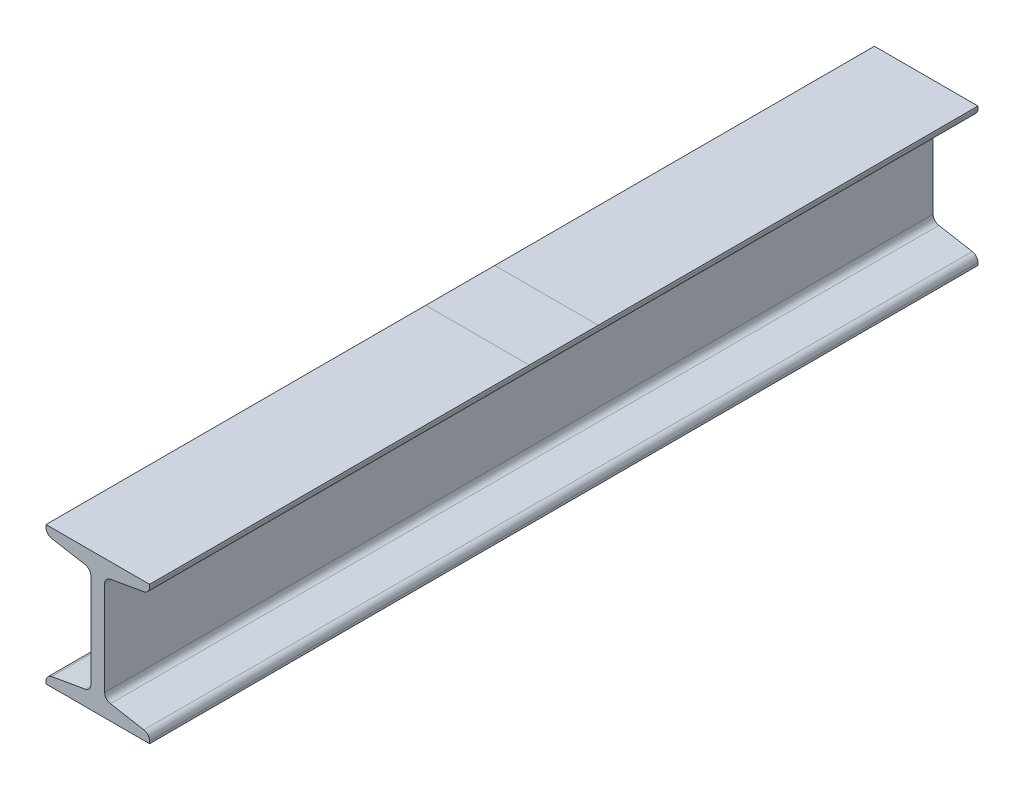
SolidWorks part; units mm, degrees
ref_plane "Front Plane" through (0, 0, 0) normal (0, 0, 1) x (1, 0, 0)
ref_plane "Top Plane" through (0, 0, 0) normal (0, 1, 0) x (1, 0, 0)
ref_plane "Right Plane" through (0, 0, 0) normal (1, 0, 0) x (0, 0, -1)
sketch "Sketch2" plane through (0, 0, 0) normal (0, 0, 1) x (1, 0, 0)
  line L0 (37.5, 50) -> (37.5, 44.0367)
  line L1 (37.5, 44.0367) -> (5, 38.3061)
  line L2 (5, 38.3061) -> (5, -38.3061)
  line L3 (5, -38.3061) -> (37.5, -44.0367)
  line L4 (37.5, -44.0367) -> (37.5, -50)
  line L5 (0, 0) -> (0, 31.6267) construction
  line L6 (0, 0) -> (-7.0282, 0) construction
  line L7 (-37.5, -44.0367) -> (-37.5, -50)
  line L8 (-5, -38.3061) -> (-37.5, -44.0367)
  line L9 (-5, 38.3061) -> (-5, -38.3061)
  line L10 (-37.5, 44.0367) -> (-5, 38.3061)
  line L11 (-37.5, 50) -> (-37.5, 44.0367)
  line L12 (-37.5, 50) -> (37.5, 50)
  line L13 (-37.5, -50) -> (37.5, -50)
  dimension "D1" = 100
  dimension "D2" = 75
  dimension "D3" = 100
  dimension "D4" = 10
extrude "Boss-Extrude1" add sketch "Sketch2" against normal blind 600
sketch "Sketch3" plane through (0, 50, 0) normal (0, 1, 0) x (1, 0, 0)
  line L0 (37.5, 600) -> (37.5, 0) construction
  line L1 (-37.5, 325) -> (37.5, 325)
  line L2 (-37.5, 325) -> (-37.5, 275)
  line L3 (-37.5, 275) -> (37.5, 275)
  line L4 (37.5, 325) -> (37.5, 275)
  line L5 (-37.5, 325) -> (37.5, 275) construction
  line L6 (-37.5, 275) -> (37.5, 325) construction
  point P0 (0, 300)
  dimension "D1" = 50
  dimension "D2" = 300
split line "Split Line1"
sketch "Sketch4" plane through (0, -50, 0) normal (0, -1, 0) x (1, 0, 0)
  line L0 (37.5, -600) -> (37.5, 0) construction
  line L1 (-37.5, 0) -> (37.5, 0)
  line L2 (-37.5, 0) -> (-37.5, -40)
  line L3 (-37.5, -40) -> (37.5, -40)
  line L4 (37.5, 0) -> (37.5, -40)
  line L6 (-37.5, -600) -> (37.5, -600)
  line L7 (-37.5, -600) -> (-37.5, -560)
  line L8 (-37.5, -560) -> (37.5, -560)
  line L9 (37.5, -600) -> (37.5, -560)
  dimension "D1" = 40
  dimension "D2" = 40
split line "Split Line2"
fillet "Fillet1" radius 5 8 edges at (37.5, 44.0367, -300) (5, 38.3061, -300) (37.5, -44.0367, -300) (5, -38.3061, -300) (-37.5, 44.0367, -300) (-5, 38.3061, -300) (-37.5, -44.0367, -300) (-5, -38.3061, -300)
